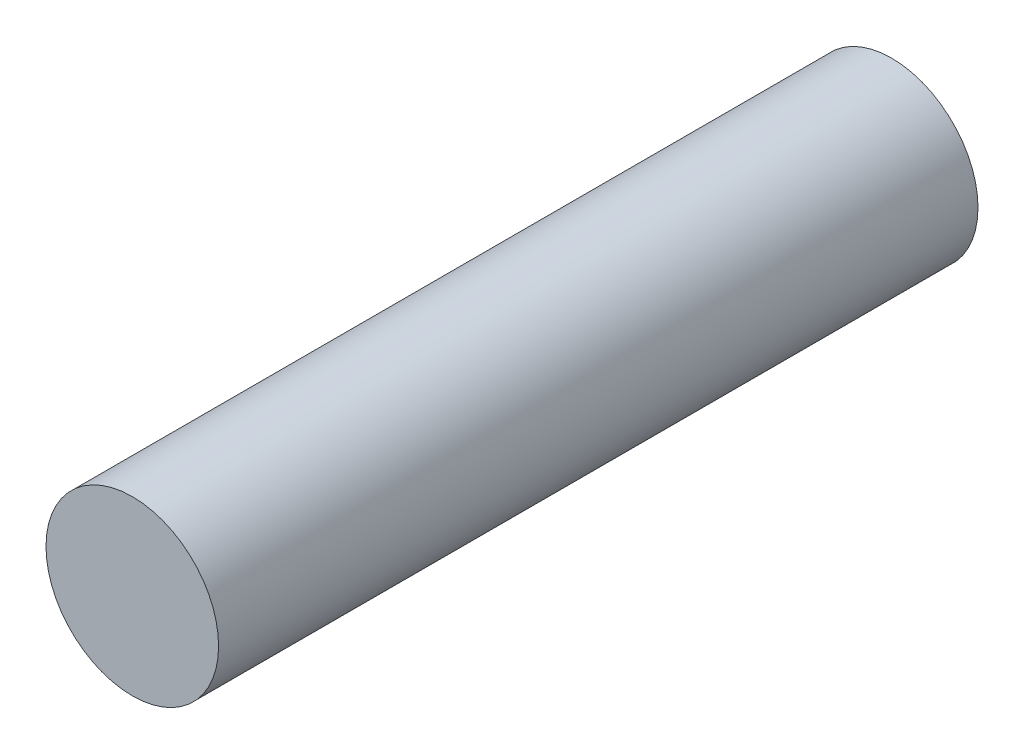
SolidWorks part; units mm, degrees
material "6061-T6 (SS)"
ref_plane "Front Plane" through (0, 0, 0) normal (0, 0, 1) x (1, 0, 0)
ref_plane "Top Plane" through (0, 0, 0) normal (0, 1, 0) x (1, 0, 0)
ref_plane "Right Plane" through (0, 0, 0) normal (1, 0, 0) x (0, 0, -1)
sketch "Sketch1" plane through (0, 0, 0) normal (1, 0, 0) x (0, 0, -1)
  line L0 (0, 0) -> (-50000, 0) construction
  line L1 (0, 0) -> (34.925, 0)
  line L2 (0, 0) -> (0, -3.9688)
  line L3 (0, -3.9688) -> (34.925, -3.9688)
  line L4 (34.925, 0) -> (34.925, -3.9688)
  dimension "D1" = 34.925
  dimension "D2" = 3.9688
revolve "Revolve1" add sketch "Sketch1" angle 360 about L0
